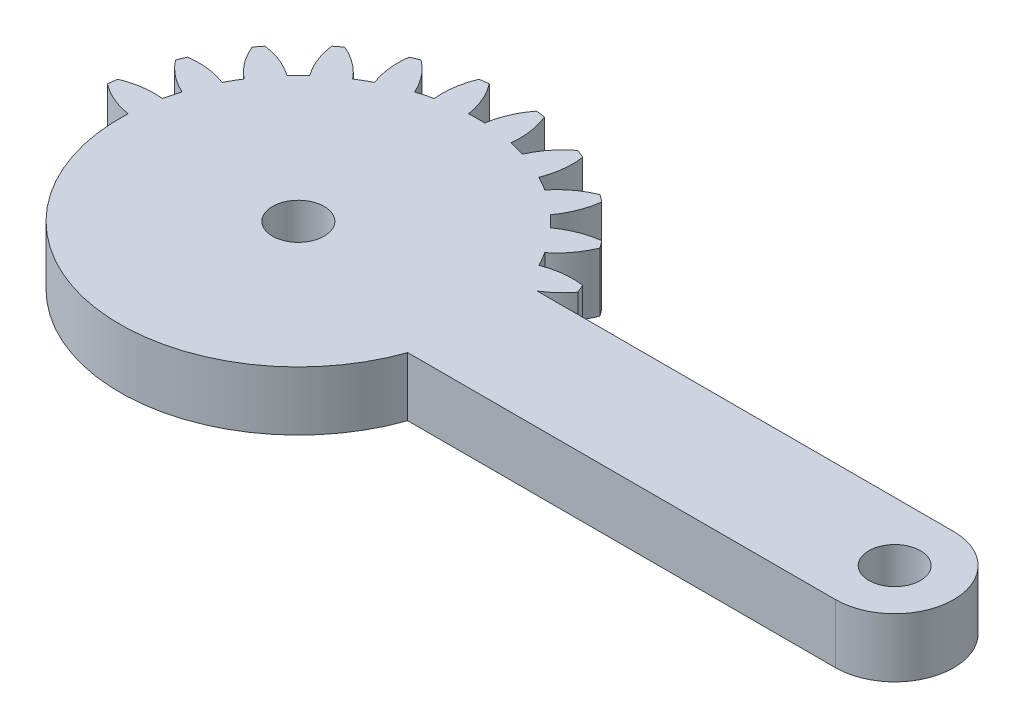
SolidWorks part; units mm, degrees
ref_plane "Front Plane" through (0, 0, 0) normal (0, 0, 1) x (1, 0, 0)
ref_plane "Top Plane" through (0, 0, 0) normal (0, 1, 0) x (1, 0, 0)
ref_plane "Right Plane" through (0, 0, 0) normal (1, 0, 0) x (0, 0, -1)
ref_plane "Plane1" through (0, 4, 0) normal (0, 1, 0) x (1, 0, 0)
sketch "Sketch1" plane through (0, 4, 0) normal (0, 1, 0) x (1, 0, 0)
  line L0 (1.3057, -4) -> (30.3066, -4)
  line L1 (30.3066, 4) -> (2.0816, 4)
  arc A0 (-24.5622, 2.2179) -> (-24.6437, 1.5991) centre (-10.1063, 0) ccw
  arc A1 (-24.6437, 1.5991) -> (-22.1869, 0.5427) centre (-21.3486, 5.8773) ccw
  arc A2 (-22.1869, 0.5427) -> (1.3057, -4) centre (-10.1063, 0) ccw
  arc A3 (30.3066, -4) -> (30.3066, 4) centre (30.3066, 0) ccw
  arc A4 (2.0816, 4) -> (3.5217, 5.3071) centre (-0.7683, 8.5867) ccw
  arc A5 (3.5217, 5.3071) -> (3.2829, 5.8838) centre (-10.1063, 0) ccw
  arc A6 (3.2829, 5.8838) -> (0.6271, 5.5703) centre (2.5684, 0.5313) ccw
  arc A7 (0.6271, 5.5703) -> (0.0844, 6.5103) centre (-10.1063, 0) ccw
  arc A8 (0.0844, 6.5103) -> (1.6838, 8.6535) centre (-3.3089, 10.711) ccw
  arc A9 (1.6838, 8.6535) -> (1.3038, 9.1487) centre (-10.1063, 0) ccw
  arc A10 (1.3038, 9.1487) -> (-1.1803, 8.1585) centre (1.999, 3.7936) ccw
  arc A11 (-1.1803, 8.1585) -> (-1.9479, 8.926) centre (-10.1063, 0) ccw
  arc A12 (-1.9479, 8.926) -> (-0.9576, 11.4102) centre (-6.3127, 12.1053) ccw
  arc A13 (-0.9576, 11.4102) -> (-1.4528, 11.7901) centre (-10.1063, 0) ccw
  arc A14 (-1.4528, 11.7901) -> (-3.596, 10.1907) centre (0.6046, 6.7975) ccw
  arc A15 (-3.596, 10.1907) -> (-4.5361, 10.7334) centre (-10.1063, 0) ccw
  arc A16 (-4.5361, 10.7334) -> (-4.2225, 13.3892) centre (-9.5751, 12.6747) ccw
  arc A17 (-4.2225, 13.3892) -> (-4.7992, 13.6281) centre (-10.1063, 0) ccw
  arc A18 (-4.7992, 13.6281) -> (-6.4554, 11.5285) centre (-1.5196, 9.3381) ccw
  arc A19 (-6.4554, 11.5285) -> (-7.5039, 11.8094) centre (-10.1063, 0) ccw
  arc A20 (-7.5039, 11.8094) -> (-7.8884, 14.4558) centre (-12.8736, 12.3803) ccw
  arc A21 (-7.8884, 14.4558) -> (-8.5072, 14.5373) centre (-10.1063, 0) ccw
  arc A22 (-8.5072, 14.5373) -> (-9.5636, 12.0806) centre (-4.2291, 11.2423) ccw
  arc A23 (-9.5636, 12.0806) -> (-10.6491, 12.0806) centre (-10.1063, 0) ccw
  arc A24 (-10.6491, 12.0806) -> (-11.7054, 14.5373) centre (-15.9836, 11.2423) ccw
  arc A25 (-11.7054, 14.5373) -> (-12.3243, 14.4558) centre (-10.1063, 0) ccw
  arc A26 (-12.3243, 14.4558) -> (-12.7088, 11.8094) centre (-7.3391, 12.3803) ccw
  arc A27 (-12.7088, 11.8094) -> (-13.7573, 11.5285) centre (-10.1063, 0) ccw
  arc A28 (-13.7573, 11.5285) -> (-15.4135, 13.6281) centre (-18.6931, 9.3381) ccw
  arc A29 (-15.4135, 13.6281) -> (-15.9901, 13.3892) centre (-10.1063, 0) ccw
  arc A30 (-15.9901, 13.3892) -> (-15.6766, 10.7334) centre (-10.6376, 12.6747) ccw
  arc A31 (-15.6766, 10.7334) -> (-16.6166, 10.1907) centre (-10.1063, 0) ccw
  arc A32 (-16.6166, 10.1907) -> (-18.7599, 11.7901) centre (-20.8173, 6.7975) ccw
  arc A33 (-18.7599, 11.7901) -> (-19.255, 11.4102) centre (-10.1063, 0) ccw
  arc A34 (-19.255, 11.4102) -> (-18.2648, 8.926) centre (-13.9, 12.1053) ccw
  arc A35 (-18.2648, 8.926) -> (-19.0324, 8.1585) centre (-10.1063, 0) ccw
  arc A36 (-19.0324, 8.1585) -> (-21.5165, 9.1487) centre (-22.2117, 3.7936) ccw
  arc A37 (-21.5165, 9.1487) -> (-21.8965, 8.6535) centre (-10.1063, 0) ccw
  arc A38 (-21.8965, 8.6535) -> (-20.2971, 6.5103) centre (-16.9038, 10.711) ccw
  arc A39 (-20.2971, 6.5103) -> (-20.8398, 5.5703) centre (-10.1063, 0) ccw
  arc A40 (-20.8398, 5.5703) -> (-23.4956, 5.8838) centre (-22.7811, 0.5313) ccw
  arc A41 (-23.4956, 5.8838) -> (-23.7344, 5.3071) centre (-10.1063, 0) ccw
  arc A42 (-23.7344, 5.3071) -> (-21.6348, 3.6509) centre (-19.4444, 8.5867) ccw
  arc A43 (-21.6348, 3.6509) -> (-21.9157, 2.6025) centre (-10.1063, 0) ccw
  arc A44 (-21.9157, 2.6025) -> (-24.5622, 2.2179) centre (-22.4867, -2.7673) ccw
  circle A45 centre (30.3066, 0) radius 1.75
  circle A46 centre (-10.1063, 0) radius 1.75
  dimension "D1" = 3.5
  dimension "D2" = 14.625
  dimension "D3" = 5.4
  dimension "D4" = 0.0844
  dimension "D5" = 4
  dimension "D6" = 0.6046
  dimension "D7" = 1.3057
  dimension "D8" = 2.0816
  dimension "D9" = 3.5217
  dimension "D10" = 1.1803
  dimension "D11" = 1.5196
  dimension "D12" = 3.3089
  dimension "D13" = 4.7992
  dimension "D14" = 9.5751
  dimension "D15" = 11.7054
  dimension "D16" = 30.3066
  dimension "D17" = 15.4135
  dimension "D18" = 18.6931
  dimension "D19" = 21.3486
  dimension "D20" = 21.9157
  dimension "D21" = 22.1869
  dimension "D22" = 22.4867
  dimension "D23" = 23.4956
extrude "Boss-Extrude1" add sketch "Sketch1" against normal blind 4
